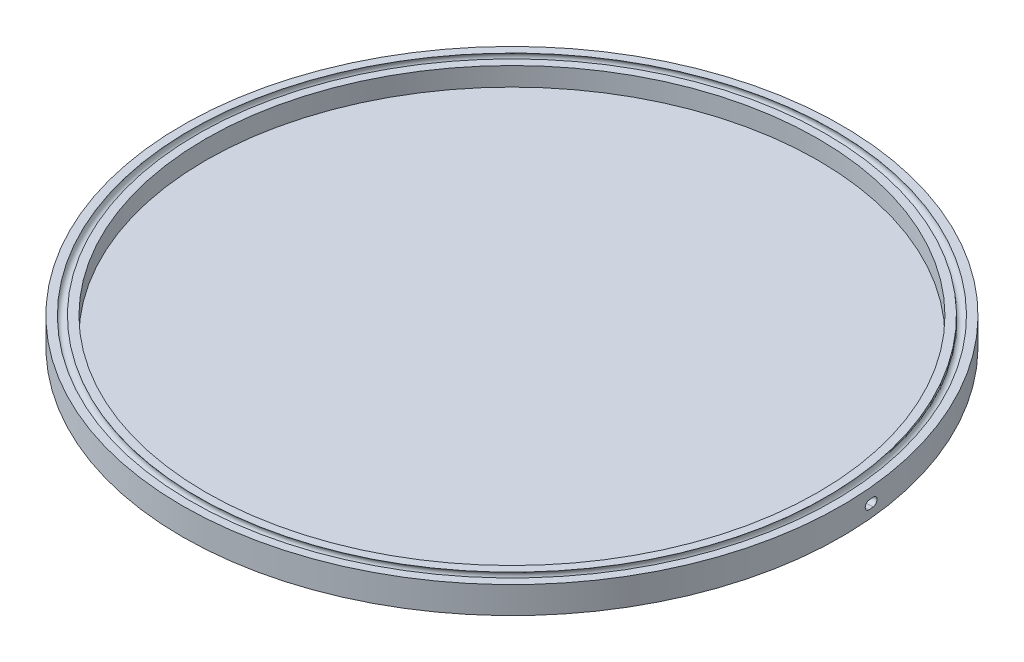
SolidWorks part; units mm, degrees
ref_plane "Front Plane" through (0, 0, 0) normal (0, 0, 1) x (1, 0, 0)
ref_plane "Top Plane" through (0, 0, 0) normal (0, 1, 0) x (1, 0, 0)
ref_plane "Right Plane" through (0, 0, 0) normal (1, 0, 0) x (0, 0, -1)
sketch "Sketch1" plane through (0, 0, 0) normal (0, 1, 0) x (1, 0, 0)
  circle A0 centre (0, 0) radius 141
  dimension "D1" = 282
extrude "Boss-Extrude1" add sketch "Sketch1" along normal blind 3.5
sketch "Sketch2" plane through (0, 3.5, 0) normal (0, 1, 0) x (1, 0, 0)
  circle A0 centre (0, 0) radius 131
  circle A1 centre (0, 0) radius 141
  dimension "D1" = 262
extrude "Boss-Extrude2" add sketch "Sketch2" along normal blind 8
sketch "Sketch3" plane through (0, 11.5, 0) normal (0, 1, 0) x (1, 0, 0)
  circle A0 centre (0, 0) radius 136
  dimension "D1" = 272
sketch "Sketch4" plane through (0, 3.5, 0) normal (0, 1, 0) x (1, 0, 0)
  line L0 (0, 0) -> (130.4139, 12.3784)
  circle A0 centre (0, 0) radius 131 construction
ref_plane "Plane1" through (0, 0, 0) normal (0.0945, 0, 0.9955) x (0.9955, 0, -0.0945)
sketch "Sketch5" plane through (0, 0, 0) normal (0.0945, 0, 0.9955) x (0.9955, 0, -0.0945)
  line L6 (136, 11.5) -> (-136, 11.5) construction
  circle A0 centre (136, 10.2) radius 2
  point P2 (141.0342, 14.4365)
  point P3 (135.8374, 9.0514)
  point P5 (145.3401, 17.2006)
  point P6 (135.8372, 10.5)
  point P7 (0, 0)
  point P8 (135.8575, 10.5)
  point P9 (135.7343, 11.8341)
  point P10 (135.7429, 12.0057)
  point P11 (135.6491, 13.88)
  point P13 (135.9689, 11.4907)
  dimension "D1" = 4
  dimension "D2" = 1.3
  dimension "D3" = 136
sweep "Cut-Sweep1" cut profiles "Sketch5" path "Sketch3"
ref_plane "Plane3" through (130.4139, 0, -12.3784) normal (-0.9955, 0, 0.0945) x (0.0945, 0, 0.9955)
sketch "Sketch6" plane through (130.4139, 0, -12.3784) normal (-0.9955, 0, 0.0945) x (0.0945, 0, 0.9955)
  line L1 (1, 5.3991) -> (-1, 5.3991) construction
  line L2 (1, 3.5991) -> (-1, 3.5991)
  line L3 (1, 7.1991) -> (-1, 7.1991)
  arc A1 (1, 3.5991) -> (1, 7.1991) centre (1, 5.3991) ccw
  arc A2 (-1, 7.1991) -> (-1, 3.5991) centre (-1, 5.3991) ccw
  point P0 (0, 5.3991)
  point P6 (0, 5.3991)
  dimension "D1" = 2
  dimension "D2" = 1.8
extrude "Cut-Extrude3" cut sketch "Sketch6" against normal blind 15 and the other way blind 5 contours L3 A2 L2 A1
equation "\"GeneralThickness\"= 3"
equation "\"D2\" = \"GeneralThickness\""
equation "\"BearBallRadio\"= 136"
equation "\"D1@Sketch1\"=\"BearBallRadio\"*2+10"
equation "\"D1@Sketch2\"=\"BearBallRadio\"*2-10"
equation "\"D1@Sketch3\"=\"BearBallRadio\"*2"
equation "\"BallDia\"=4"
equation "\"D1@Sketch5\"=\"BallDia\""
equation "\"D3@Sketch5\"=\"BearBallRadio\""
